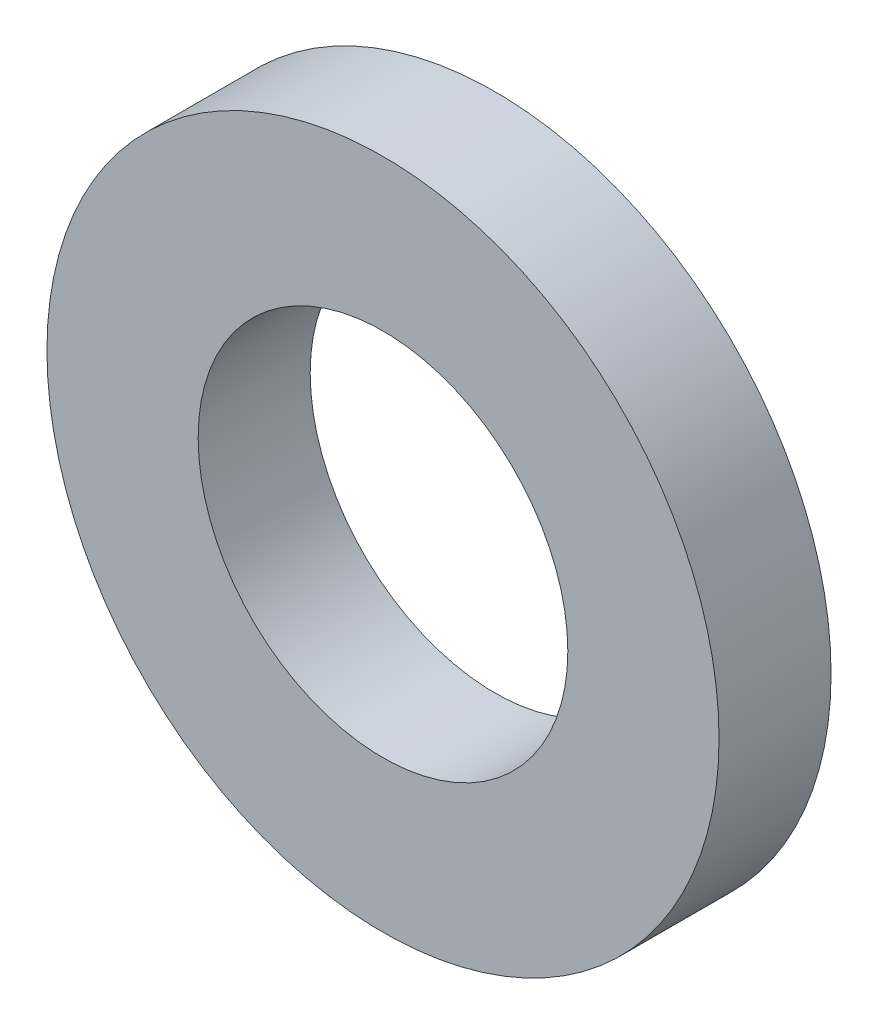
SolidWorks part; units mm, degrees
ref_plane "前视基准面" through (0, 0, 0) normal (0, 0, 1) x (1, 0, 0)
ref_plane "上视基准面" through (0, 0, 0) normal (0, 1, 0) x (1, 0, 0)
ref_plane "右视基准面" through (0, 0, 0) normal (1, 0, 0) x (0, 0, -1)
other "Configuration Table"
sketch "草图1" plane through (0, 0, 0) normal (0, 0, 1) x (1, 0, 0)
  circle A0 centre (0, 0) radius 3
  circle A1 centre (0, 0) radius 1.65
extrude "硅胶减振圈包络" add sketch "草图1" along normal blind 1
